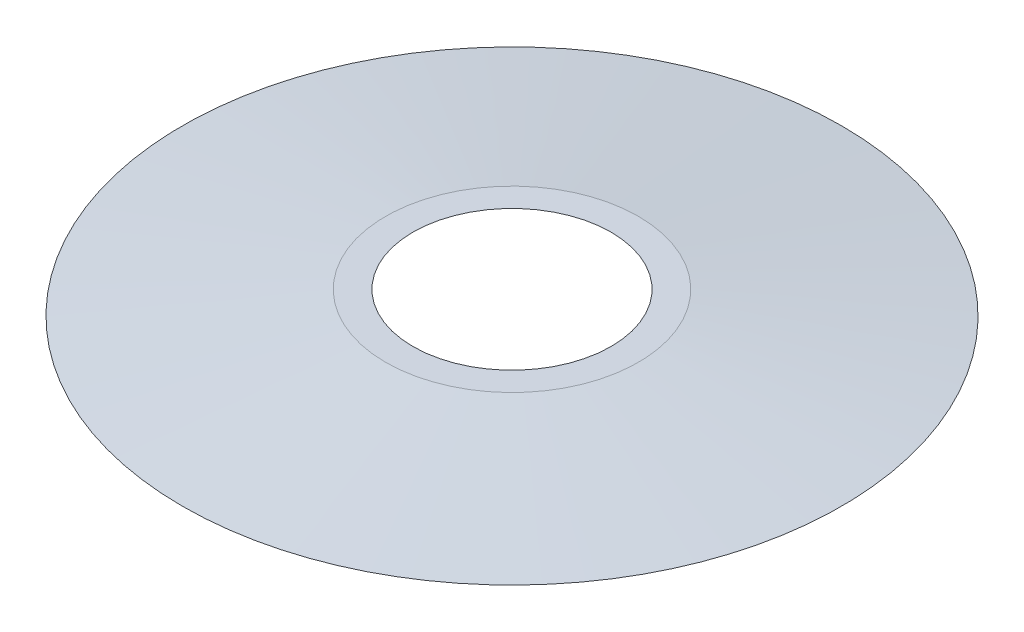
SolidWorks part; units mm, degrees
ref_plane "前视基准面" through (0, 0, 0) normal (0, 0, 1) x (1, 0, 0)
ref_plane "上视基准面" through (0, 0, 0) normal (0, 1, 0) x (1, 0, 0)
ref_plane "右视基准面" through (0, 0, 0) normal (1, 0, 0) x (0, 0, -1)
other "Configuration Table"
sketch "草图1" plane through (0, 0, 0) normal (0, 0, 1) x (1, 0, 0)
  line L0 (14.6523, 1.7081) -> (18.6992, 1.7081)
  line L1 (37.6953, -1.7081) -> (48.7461, -1.7081)
  line L2 (0, 0) -> (0, -12.9279)
  line L4 (18.6992, 1.7081) -> (48.7461, -1.7081)
  line L5 (14.6523, 1.7081) -> (37.6953, -1.7081)
  point P6 (4.6992, 1.7081)
  point P10 (4.6992, -1.7081)
revolve "旋转1" add sketch "草图1" angle 360 about L2
